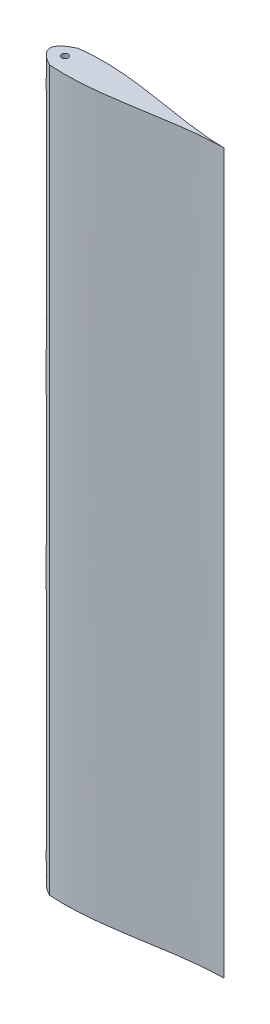
SolidWorks part; units mm, degrees
ref_plane "Front Plane" through (0, 0, 0) normal (0, 0, 1) x (1, 0, 0)
ref_plane "Top Plane" through (0, 0, 0) normal (0, 1, 0) x (1, 0, 0)
ref_plane "Right Plane" through (0, 0, 0) normal (1, 0, 0) x (0, 0, -1)
sketch "Sketch2" plane through (0, 0, 0) normal (0, 1, 0) x (1, 0, 0)
  spline S0 degree 2 poles (-10.5008, 1.8522) (-14.5062, 0.0004) (-10.5008, -2.1478) knots 0 0 0 1 1 1
  spline S1 degree 3 poles (-10.5008, 1.8522) (-2.7189, 2.8279) (4.7937, -0.1169) (12.4992, 0) knots 0 0 0 0 1 1 1 1
  spline S2 degree 3 poles (-10.5008, -2.1478) (-2.7367, -2.7095) (4.7884, 0.1121) (12.4992, 0) knots 0 0 0 0 1 1 1 1
  point P1 (0, 0)
  dimension "D1" = 4
  dimension "D2" = 25
  dimension "D3" = 2
extrude "Boss-Extrude1" add sketch "Sketch2" along normal blind 100 contours S0 S2 S1
sketch "Sketch3" plane through (0, 100, 0) normal (0, 1, 0) x (1, 0, 0)
  circle A0 centre (-10.5035, 0) radius 0.4543
  parabola Q0 (-10.5008, 1.8522) -> (-10.5008, -2.1478) focus (-12.0049, -0.0552) apex (-12.5028, -0.0368) construction
  point P7 (-12.5035, -0.0737)
  dimension "D1" = 2
extrude "Cut-Extrude1" cut sketch "Sketch3" against normal blind 100 contours A0
